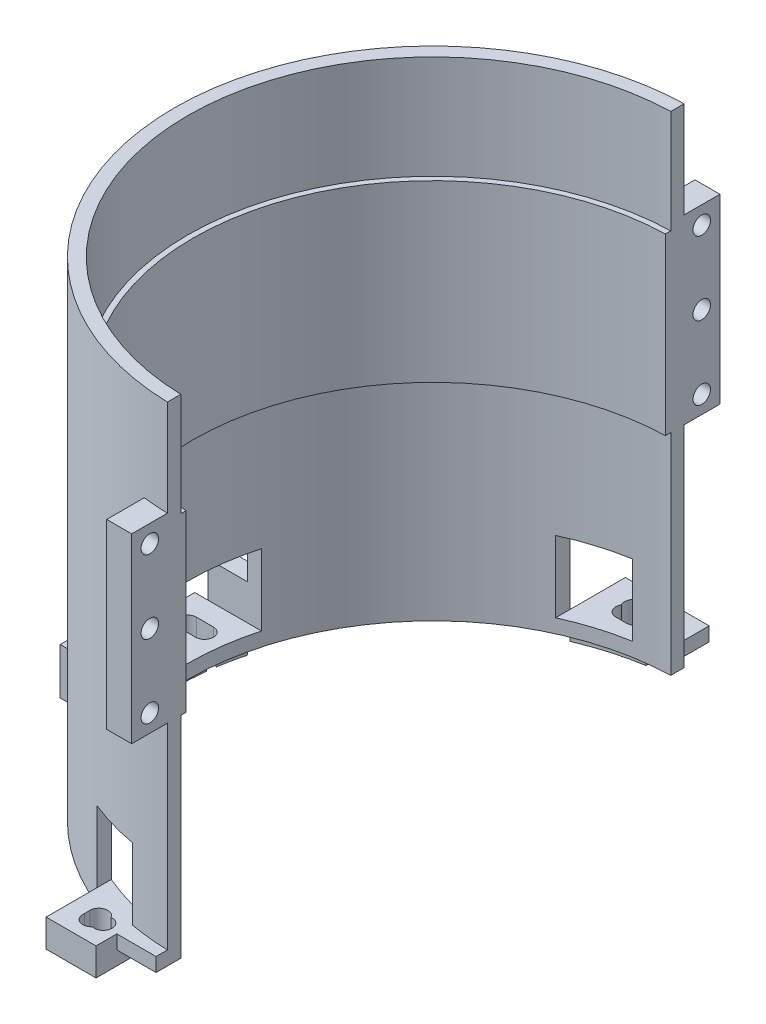
SolidWorks part; units mm, degrees
material "PLA"
ref_plane "Front Plane" through (0, 0, 0) normal (0, 0, 1) x (1, 0, 0)
ref_plane "Top Plane" through (0, 0, 0) normal (0, 1, 0) x (1, 0, 0)
ref_plane "Right Plane" through (0, 0, 0) normal (1, 0, 0) x (0, 0, -1)
sketch "Sketch1" plane through (0, 0, 0) normal (0, 1, 0) x (1, 0, 0)
  line L0 (0, 72.5) -> (0, -72.5) construction
  line L3 (0, -67.5) -> (0, -82.3274)
  line L4 (0, -82.3274) -> (-5, -82.3274)
  line L5 (-5, -72.3274) -> (-5, -82.3274)
  line L7 (0, 67.5) -> (0, 82.5)
  line L8 (0, 82.5) -> (-5, 82.5)
  line L9 (-5, 72.3274) -> (-5, 82.5)
  arc A0 (0, 67.5) -> (0, -67.5) centre (0, 0) ccw
  arc A1 (-5, 72.3274) -> (-5, -72.3274) centre (0, 0) ccw
  point P10 (-5, -72.3274)
  dimension "D1" = 135
  dimension "D2" = 145
  dimension "D3" = 10
  dimension "D4" = 10
  dimension "D5" = 5
  dimension "D6" = 5
extrude "Boss-Extrude1" add sketch "Sketch1" along normal blind 10
sketch "Sketch2" plane through (0, 0, 0) normal (0, -1, 0) x (1, 0, 0)
  line L0 (0, 72.5) -> (0, 68.5)
  line L2 (0, -72.5) -> (0, -68.5)
  arc A0 (0, 68.5) -> (0, -68.5) centre (0, 0) ccw
  arc A1 (0, 72.5) -> (0, -72.5) centre (0, 0) ccw
  dimension "D1" = 137
extrude "Boss-Extrude2" add sketch "Sketch2" along normal blind 73
sketch "Sketch3" plane through (0, -73, 0) normal (0, -1, 0) x (1, 0, 0)
  line L0 (-20.25, -68.5) -> (-20.25, 92.8167) construction
  line L2 (-85.75, 30.25) -> (-85.75, -30.25)
  line L3 (-85.75, -30.25) -> (-65.25, -30.25)
  line L9 (-20.25, -89) -> (20.25, -68.5) construction
  line L10 (-20.25, -68.5) -> (20.25, -89) construction
  line L11 (0, 0) -> (-113.2358, 0) construction
  line L13 (-25.25, -67.9609) -> (-25.25, -68.5)
  line L14 (-63.3537, -35.25) -> (-65.25, -35.25)
  line L15 (-65.25, -30.25) -> (-65.25, -126.0931) construction
  line L16 (-20.25, -68.5) -> (-129.7637, -68.5) construction
  line L18 (-59.5558, -52.1992) -> (-60.8059, -54.3063) construction
  line L19 (-59.5558, -52.1992) -> (-48.9492, -62.8058) construction
  line L20 (-54.2525, -57.5025) -> (-63.6883, -66.9383) construction
  line L21 (-59.5558, -52.1992) -> (-61.9488, -51.6738) construction
  line L23 (-65.25, -68.5) -> (-50.6267, -53.8767) construction
  line L25 (-48.9492, -62.8058) -> (-46.5562, -63.3312) construction
  line L44 (0, -69.5) -> (0, -88)
  line L45 (-84.75, 29.25) -> (-66.3377, 29.25)
  line L46 (-84.75, 29.25) -> (-84.75, -29.25)
  line L47 (-84.75, -29.25) -> (-66.3377, -29.25)
  line L49 (19.25, -69.5) -> (18.2744, -69.5)
  line L51 (19.25, -88) -> (18.2744, -88)
  line L52 (-19.25, -69.5) -> (-19.25, -88)
  line L53 (19.25, -69.5) -> (-19.25, -88) construction
  line L54 (19.25, -88) -> (-19.25, -69.5) construction
  line L55 (0, -69.5) -> (-19.25, -69.5)
  line L56 (0, -88) -> (-19.25, -88)
  line L57 (0, 69.5) -> (-19.25, 69.5)
  line L58 (0, 69.5) -> (0, 88)
  line L59 (0, 88) -> (-19.25, 88)
  line L60 (-19.25, 69.5) -> (-19.25, 88)
  arc A1 (0, 72.5) -> (0, -72.5) centre (0, 0) ccw construction
  circle A9 centre (-75.5, 20) radius 2.5
  circle A10 centre (-75.5, 0) radius 2.5
  circle A11 centre (-75.5, -20) radius 2.5
  arc A12 (-66.3377, 29.25) -> (-66.3377, -29.25) centre (0, 0) ccw
  circle A13 centre (-10, -78.75) radius 2.5
  circle A14 centre (-10, 78.75) radius 2.5
  point P1 (-20.25, -78.75)
  point P7 (-95, 0)
  point P8 (-85.75, 0)
  point P9 (0, -95)
  point P10 (0, -78.75)
  point P15 (0, -89)
  point P22 (0, -78.75)
  point P39 (-58.7595, -62.0095)
  point P42 (-54.2525, -57.5025)
  point P68 (-75.5, 29.25)
  point P70 (-75.5, -29.25)
  dimension "D21" = 5
  dimension "D22" = 5
  dimension "D23" = 5
  dimension "D8" = 5
  dimension "D2" = 60.5
  dimension "D3" = 20.5
  dimension "D4" = 9.25
  dimension "D5" = 20.5
  dimension "D6" = 40.5
  dimension "D9" = 1
  dimension "D11" = 5
  dimension "D17" = 45
  dimension "D19" = 1
  dimension "D20" = 58.5
  dimension "D25" = 20
  dimension "D26" = 20
sketch "Sketch4" plane through (0, -73, 0) normal (0, -1, 0) x (1, 0, 0)
  line L0 (0, 0) -> (0, -95) construction
  line L1 (-68.5, -20.1966) -> (-89, -20.1966)
  line L2 (-68.5, -20.1966) -> (-68.5, 20.3034)
  line L3 (-68.5, 20.3034) -> (-89, 20.3034)
  line L4 (-89, -20.1966) -> (-89, 20.3034)
  line L5 (-68.5, -20.1966) -> (-89, 20.3034) construction
  line L6 (-68.5, 20.3034) -> (-89, -20.1966) construction
  line L7 (-70.1515, 18.3034) -> (-87, 18.3034)
  line L8 (-30.25, -85.75) -> (30.25, -85.75)
  line L9 (-30.25, -85.75) -> (-30.25, -65.25)
  line L10 (-30.25, -65.25) -> (30.25, -65.25)
  line L11 (30.25, -85.75) -> (30.25, -65.25)
  line L12 (-30.25, -85.75) -> (30.25, -65.25) construction
  line L13 (-30.25, -65.25) -> (30.25, -85.75) construction
  line L14 (-30.25, 65.25) -> (30.25, 65.25)
  line L15 (-30.25, 65.25) -> (-30.25, 85.75)
  line L16 (-30.25, 85.75) -> (30.25, 85.75)
  line L17 (30.25, 65.25) -> (30.25, 85.75)
  line L18 (-30.25, 65.25) -> (30.25, 85.75) construction
  line L19 (-30.25, 85.75) -> (30.25, 65.25) construction
  line L20 (-87, 18.3034) -> (-87, -18.1966)
  line L21 (-87, -18.1966) -> (-70.1793, -18.1966)
  line L22 (-28.25, -66.7697) -> (-28.25, -83.75)
  line L23 (-28.25, -83.75) -> (-11.75, -83.75)
  line L24 (-11.75, -83.75) -> (-11.75, -71.5415)
  line L25 (-27, 67.2848) -> (-27, 80)
  line L26 (-27, 80) -> (-13, 80)
  line L27 (-13, 80) -> (-13, 71.325)
  circle A0 centre (0, 0) radius 95
  circle A1 centre (-78.75, 10.0534) radius 2.5
  circle A2 centre (-78.75, -9.9466) radius 2.5
  arc A3 (0, 72.5) -> (0, -72.5) centre (0, 0) ccw construction
  arc A4 (-70.1515, 18.3034) -> (-70.1793, -18.1966) centre (0, 0) ccw
  circle A5 centre (-20, -75.5) radius 2.5
  arc A6 (-28.25, -66.7697) -> (-11.75, -71.5415) centre (0, 0) ccw
  circle A7 centre (-20, 73) radius 2.5
  arc A8 (-27, 67.2848) -> (-13, 71.325) centre (0, 0) cw
  point P3 (-78.75, 0.0534)
  point P8 (-95, 0)
  point P10 (0, -75.5)
  point P15 (0, 75.5)
  point P16 (0, -95)
  point P22 (0, 95)
  point P26 (-78.75, 20.3034)
  point P37 (-30.25, -75.5)
  arc M22 (0, 72.5) -> (0, -72.5) centre (0, 0) ccw
  dimension "D1" = 190
  dimension "D11" = 5
  dimension "D12" = 5
  dimension "D13" = 10.25
  dimension "D18" = 5
  dimension "D23" = 5
  dimension "D2" = 20.5
  dimension "D3" = 40.5
  dimension "D4" = 26.5
  dimension "D5" = 20.5
  dimension "D6" = 60.5
  dimension "D7" = 29.75
  dimension "D8" = 20.5
  dimension "D9" = 60.5
  dimension "D10" = 29.75
  dimension "D14" = 10.25
  dimension "D15" = 2
  dimension "D16" = 2
  dimension "D17" = 2
  dimension "D19" = 10.25
  dimension "D20" = 2
  dimension "D21" = 2
  dimension "D22" = 8.25
  dimension "D24" = 73
  dimension "D25" = 20
  dimension "D26" = 7
  dimension "D27" = 7
  dimension "D28" = 7
extrude "Boss-Extrude3" add sketch "Sketch4" along normal mid plane 7.8 contours L27 L26 L25 A7 M22 | L20 L21 L7 A2 A1 M22 | L23 L24 L22 A5 M22
sketch "Sketch5" plane through (0, -69.1, 0) normal (0, 1, 0) x (1, 0, 0)
  circle A0 centre (-20, 75.5) radius 2.5 construction
  point P0 (-17.5, 75.5)
  point P1 (0, 0)
sketch "Sketch6" plane through (-5, 0, 0) normal (-1, 0, 0) x (0, 0, 1)
  line L0 (-77.4137, 10) -> (-77.4137, 5) construction
  line L1 (-82.5, 10) -> (-72.3274, 10) construction
  line L2 (-77.4137, 5) -> (-82.5, 5) construction
  line L3 (-82.5, 10) -> (-82.5, 0) construction
  line L4 (82.3274, 10) -> (82.3274, 0) construction
  line L6 (77.4124, 5) -> (72.3274, 5) construction
  line L7 (72.3274, 10) -> (72.3274, 0) construction
  circle A0 centre (77.4124, 5) radius 2.45
  circle A1 centre (-77.4137, 5) radius 2.45
  dimension "D1" = 4.9
  dimension "D2" = 4.9
  dimension "D3" = 4.915
extrude "Cut-Extrude1" cut sketch "Sketch6" against normal blind 13.9
sketch "Sketch7" plane through (0, 0, 80) normal (0, 0, 1) x (1, 0, 0)
  line L1 (-27, -69.1) -> (-13, -69.1)
  line L2 (-27, -69.1) -> (-27, -49.1)
  line L3 (-27, -49.1) -> (-13, -49.1)
  line L4 (-13, -69.1) -> (-13, -49.1)
  dimension "D1" = 20
extrude "Cut-Extrude2" cut sketch "Sketch7" against normal blind 23.9
sketch "Sketch8" plane through (0, -69.1, 0) normal (0, 1, 0) x (1, 0, 0)
  circle A0 centre (-20, -73) radius 4.8698
sketch "Sketch10" plane through (0, -69.1, 0) normal (0, 1, 0) x (1, 0, 0)
  line L0 (-13, -71.325) -> (-13, -75.6625)
  line L1 (-13, -80) -> (-13, -71.325) construction
  line L2 (-13, -75.6625) -> (0, -75.6625)
  line L3 (0, -75.6625) -> (0, -72.5)
  arc A0 (-13, -71.325) -> (0, -72.5) centre (0, 0) ccw construction
  arc A1 (-13, -71.325) -> (0, -72.5) centre (0, 0) ccw
extrude "Boss-Extrude4" add sketch "Sketch10" against normal blind 3.9
sketch "Sketch11" plane through (0, 10, 0) normal (0, 1, 0) x (1, 0, 0)
  line L0 (0, 82.5) -> (0, -82.3274) construction
  circle A0 centre (0, 0.0863) radius 67.4137
sketch "Sketch12" plane through (0, 0, 82.3274) normal (0, 0, 1) x (1, 0, 0)
  line L4 (-5, 0) -> (0, 0)
  line L5 (0, 0) -> (0, 10)
  line L6 (0, 10) -> (-5, 10)
  line L7 (-5, 10) -> (-5, 0)
  line L8 (-5, 0) -> (0, 0)
  line L9 (0, 0) -> (0, 10)
  line L10 (0, 10) -> (-5, 10)
  line L11 (-5, 10) -> (-5, 0)
  dimension "D1" = 0
extrude "Boss-Extrude5" add sketch "Sketch12" along normal blind 0.17
sketch "Sketch13" plane through (0, -73, 0) normal (0, -1, 0) x (1, 0, 0)
  circle A0 centre (0, 0) radius 68.75
  dimension "D1" = 137.5
extrude "Cut-Extrude3" cut sketch "Sketch13" against normal up to surface (73 mm away) up to face at (-34, 0, 0)
sketch "Sketch14" plane through (0, 10, 0) normal (0, 1, 0) x (1, 0, 0)
  line L6 (-5, -72.3274) -> (-5, -82.4974)
  line L7 (-5, -82.4974) -> (0, -82.4974)
  line L8 (0, -82.4974) -> (0, -67.5)
  line L9 (0, 67.5) -> (0, 82.5)
  line L10 (0, 82.5) -> (-5, 82.5)
  line L11 (-5, 82.5) -> (-5, 72.3274)
  line L12 (-5, -72.3274) -> (-5, -82.4974)
  line L13 (-5, -82.4974) -> (0, -82.4974)
  line L14 (0, -82.4974) -> (0, -67.5)
  line L15 (0, 67.5) -> (0, 82.5)
  line L16 (0, 82.5) -> (-5, 82.5)
  line L17 (-5, 82.5) -> (-5, 72.3274)
  arc A2 (-5, 72.3274) -> (-5, -72.3274) centre (0, 0) ccw
  arc A3 (0, 67.5) -> (0, -67.5) centre (0, 0) ccw
  arc A4 (-5, 72.3274) -> (-5, -72.3274) centre (0, 0) ccw
  arc A5 (0, 67.5) -> (0, -67.5) centre (0, 0) ccw
  dimension "D1" = 0
extrude "Boss-Extrude6" add sketch "Sketch14" along normal blind 27
sketch "Sketch15" plane through (0, 37, 0) normal (0, 1, 0) x (1, 0, 0)
  line L0 (0, -68.75) -> (0, -72.5)
  line L1 (0, 68.75) -> (0, -68.2) construction
  line L2 (0, 68.75) -> (0, 68.2)
  line L3 (0, -68.75) -> (0, -68.2)
  line L4 (0, -75.6625) -> (0, -68.75)
  line L5 (-13, -75.6625) -> (0, -75.6625)
  line L6 (-13, -71.325) -> (-13, -75.6625)
  line L7 (0, 68.75) -> (0, 72.5)
  line L11 (0, 68.75) -> (0, 72.5)
  arc A0 (-13, -71.325) -> (0, -72.5) centre (0, 0) ccw construction
  arc A1 (-13, -71.325) -> (0, -72.5) centre (0, 0) ccw
  arc A2 (0, 68.2) -> (0, -68.2) centre (0, 0) ccw
  arc A7 (0, 68.75) -> (0, -68.75) centre (0, 0) ccw
  arc A8 (-27, -67.2848) -> (-13, -71.325) centre (0, 0) ccw
  arc A9 (-70.1515, -18.3034) -> (-27, -67.2848) centre (0, 0) ccw
  arc A10 (-70.1793, 18.1966) -> (-70.1515, -18.3034) centre (0, 0) ccw
  arc A11 (-28.25, 66.7697) -> (-70.1793, 18.1966) centre (0, 0) ccw
  arc A12 (-11.75, 71.5415) -> (-28.25, 66.7697) centre (0, 0) ccw
  arc A13 (0, 72.5) -> (-11.75, 71.5415) centre (0, 0) ccw
  arc A14 (0, 68.75) -> (0, -68.75) centre (0, 0) ccw
  arc A15 (-27, -67.2848) -> (-13, -71.325) centre (0, 0) ccw
  arc A16 (-70.1515, -18.3034) -> (-27, -67.2848) centre (0, 0) ccw
  arc A17 (-70.1793, 18.1966) -> (-70.1515, -18.3034) centre (0, 0) ccw
  arc A18 (-28.25, 66.7697) -> (-70.1793, 18.1966) centre (0, 0) ccw
  arc A19 (-11.75, 71.5415) -> (-28.25, 66.7697) centre (0, 0) ccw
  arc A20 (0, 72.5) -> (-11.75, 71.5415) centre (0, 0) ccw
  arc M14 (-5, 72.3274) -> (-5, -72.3274) centre (0, 0) ccw
  line M17 (0, -82.4974) -> (0, -67.5)
  line M19 (0, 67.5) -> (0, 82.5)
  dimension "D2" = 136.4
  dimension "D1" = 0
extrude "Boss-Extrude7" add sketch "Sketch15" along normal blind 27 contours A20 A1 A14 M19 M14 M17 | A14 A2 M19 M17
sketch "Sketch16" plane through (0, -73, 0) normal (0, -1, 0) x (1, 0, 0)
  line L2 (0, -68.2) -> (0, -67.5)
  line L3 (0, 67.5) -> (0, 68.2)
  line L4 (0, -68.2) -> (0, -67.5)
  line L5 (0, 67.5) -> (0, 68.2)
  arc A2 (0, 68.2) -> (0, -68.2) centre (0, 0) ccw
  arc A3 (0, 67.5) -> (0, -67.5) centre (0, 0) ccw
  arc A4 (0, 68.2) -> (0, -68.2) centre (0, 0) ccw
  arc A5 (0, 67.5) -> (0, -67.5) centre (0, 0) ccw
  dimension "D1" = 0
sketch "Sketch17" plane through (0, 0, 0) normal (0, -1, 0) x (1, 0, 0)
  line L0 (0, 68.2) -> (0, 68.75)
  line L1 (0, -68.2) -> (0, -68.75)
  line L2 (0, -68.2) -> (0, -67.5)
  line L3 (0, 67.5) -> (0, 68.2)
  arc A0 (0, 68.75) -> (0, -68.75) centre (0, 0) ccw construction
  arc A1 (0, 68.75) -> (0, -68.75) centre (0, 0) ccw
  arc A2 (0, 68.2) -> (0, -68.2) centre (0, 0) ccw
  arc A3 (0, 67.5) -> (0, -67.5) centre (0, 0) ccw
  arc A4 (0, 68.2) -> (0, -68.2) centre (0, 0) ccw
  dimension "D1" = 0
extrude "Boss-Extrude8" add sketch "Sketch17" along normal up to surface (73 mm away) up to face at (-28.7427, -73, 7.1905)
sketch "Sketch18" plane through (0, 37, 0) normal (0, 1, 0) x (1, 0, 0)
  line L0 (0, 67.5) -> (0, -67.25) construction
  line L1 (0, -67.25) -> (0, -67.5)
  line L2 (0, 67.5) -> (0, 67.25)
  arc A0 (0, 67.25) -> (0, -67.25) centre (0, 0) ccw
  arc A2 (0, 67.5) -> (0, -67.5) centre (0, 0) ccw construction
  arc A3 (0, 67.5) -> (0, -67.5) centre (0, 0) ccw
  dimension "D1" = 134.5
extrude "Boss-Extrude9" add sketch "Sketch18" against normal up to surface (37 mm away) up to face at (-2.5004, 0, -77.4676)
sketch "Sketch19" plane through (0, 0, 0) normal (0, -1, 0) x (1, 0, 0)
  line L2 (0, -68.2) -> (0, -67.25)
  line L3 (0, 67.25) -> (0, 68.2)
  line L4 (0, -68.2) -> (0, -67.25)
  line L5 (0, 67.25) -> (0, 68.2)
  arc A2 (0, 68.2) -> (0, -68.2) centre (0, 0) ccw
  arc A3 (0, 67.25) -> (0, -67.25) centre (0, 0) ccw
  arc A4 (0, 68.2) -> (0, -68.2) centre (0, 0) ccw
  arc A5 (0, 67.25) -> (0, -67.25) centre (0, 0) ccw
  dimension "D1" = 0
extrude "Boss-Extrude10" add sketch "Sketch19" along normal blind 14
sketch "Sketch20" plane through (0, 37, 0) normal (0, 1, 0) x (1, 0, 0)
  line L2 (0, 67.25) -> (0, 68.2)
  line L3 (0, -68.2) -> (0, -67.25)
  line L4 (0, 67.25) -> (0, 68.2)
  line L5 (0, -68.2) -> (0, -67.25)
  arc A2 (0, 68.2) -> (0, -68.2) centre (0, 0) ccw
  arc A3 (0, 67.25) -> (0, -67.25) centre (0, 0) ccw
  arc A4 (0, 68.2) -> (0, -68.2) centre (0, 0) ccw
  arc A5 (0, 67.25) -> (0, -67.25) centre (0, 0) ccw
  dimension "D1" = 0
extrude "Cut-Extrude4" cut sketch "Sketch20" against normal blind 2
sketch "Sketch21" plane through (0, 0, 80) normal (0, 0, 1) x (1, 0, 0)
  line L4 (-13, -49.1) -> (-27, -49.1)
  line L5 (-27, -49.1) -> (-27, -69.1)
  line L6 (-27, -69.1) -> (-13, -69.1)
  line L7 (-13, -69.1) -> (-13, -49.1)
  line L8 (-13, -49.1) -> (-27, -49.1)
  line L9 (-27, -49.1) -> (-27, -69.1)
  line L10 (-27, -69.1) -> (-13, -69.1)
  line L11 (-13, -69.1) -> (-13, -49.1)
  dimension "D1" = 0
extrude "Cut-Extrude5" cut sketch "Sketch21" against normal blind 22
sketch "Sketch23" plane through (0, 0, 0) normal (0, -1, 0) x (1, 0, 0)
  line L3 (0, 72.5) -> (0, 82.4974)
  line L4 (0, 82.4974) -> (-5, 82.4974)
  line L5 (-5, 82.4974) -> (-5, 72.3274)
  line L6 (0, 72.5) -> (0, 82.4974)
  line L7 (0, 82.4974) -> (-5, 82.4974)
  line L8 (-5, 82.4974) -> (-5, 72.3274)
  arc A1 (0, 72.5) -> (-5, 72.3274) centre (0, 0) ccw
  arc A2 (0, 72.5) -> (-5, 72.3274) centre (0, 0) ccw
  dimension "D1" = 0
extrude "Boss-Extrude11" add sketch "Sketch23" along normal up to surface (14 mm away) up to face at (-33.8625, -14, 0)
sketch "Sketch24" plane through (0, 0, 0) normal (1, 0, 0) x (0, 0, -1)
  line L0 (-77.4124, 5) -> (-77.4124, -14) construction
  line L1 (-72.5, -14) -> (-82.4974, -14) construction
  line L2 (-77.4124, 5) -> (-77.4124, 37) construction
  line L3 (-82.4974, 37) -> (-72.5, 37) construction
  circle A0 centre (-77.4124, -9.05) radius 2.45
  circle A1 centre (-77.4124, 32.05) radius 2.45
  circle A2 centre (-77.4124, 11.5) radius 2.45
  point P10 (-77.4124, -11.5)
  point P13 (-77.4124, 34.5)
  dimension "D1" = 4.9
  dimension "D3" = 4.9
  dimension "D5" = 4.9
  dimension "D2" = 2.5
  dimension "D4" = 2.5
  dimension "D6" = 25.5
sketch "Sketch25" plane through (0, 0, 0) normal (1, 0, 0) x (0, 0, -1)
  circle A0 centre (-77.4124, 5) radius 2.45
extrude "Boss-Extrude12" add sketch "Sketch25" against normal up to surface (5 mm away) up to face at (-5, 5, 79.8624)
extrude "Cut-Extrude6" cut sketch "Sketch24" against normal blind 22 contours A0 | A1 | A2
sketch "Sketch26" plane through (0, 0, 0) normal (1, 0, 0) x (0, 0, -1)
  circle A0 centre (77.4137, 5) radius 2.45 construction
  circle A1 centre (77.4137, 5) radius 2.45
extrude "Boss-Extrude13" add sketch "Sketch26" against normal up to surface (5 mm away) up to face at (-5, 5, -74.9637)
sketch "Sketch27" plane through (0, 0, 0) normal (0, -1, 0) x (1, 0, 0)
  line L3 (-5, -72.3274) -> (-5, -82.5)
  line L4 (-5, -82.5) -> (0, -82.5)
  line L5 (0, -82.5) -> (0, -72.5)
  line L6 (-5, -72.3274) -> (-5, -82.5)
  line L7 (-5, -82.5) -> (0, -82.5)
  line L8 (0, -82.5) -> (0, -72.5)
  arc A1 (-5, -72.3274) -> (0, -72.5) centre (0, 0) ccw
  arc A2 (-5, -72.3274) -> (0, -72.5) centre (0, 0) ccw
  dimension "D1" = 0
extrude "Boss-Extrude14" add sketch "Sketch27" along normal up to surface (14 mm away) up to face at (-33.8625, -14, 0)
sketch "Sketch28" plane through (0, 64, 0) normal (0, 1, 0) x (1, 0, 0)
  line L0 (-72.5, -0.0552) -> (-33.8601, -0.0552) construction
  arc A0 (-70.1793, 18.1966) -> (-70.1515, -18.3034) centre (0, 0) ccw construction
ref_plane "Plane2" through (0, 0, 0.0552) normal (0, 0, 1) x (1, 0, 0)
sketch "Sketch29" plane through (0, 0, 0) normal (1, 0, 0) x (0, 0, -1)
  line L0 (82.5, 37) -> (82.5, -14) construction
  line L1 (72.5, 37) -> (82.5, 37) construction
  circle A0 centre (77.41, 32.05) radius 2.45
  circle A1 centre (77.41, 11.5) radius 2.45
  circle A2 centre (77.41, -9.05) radius 2.45
  dimension "D1" = 4.9
  dimension "D2" = 4.9
  dimension "D3" = 4.9
  dimension "D6" = 20.55
  dimension "D4" = 5.09
  dimension "D5" = 4.95
  dimension "D7" = 20.55
extrude "Cut-Extrude7" cut sketch "Sketch29" against normal blind 22
sketch "Sketch30" plane through (0, -69.1, 0) normal (0, 1, 0) x (1, 0, 0)
  circle A0 centre (-20, -75.71) radius 2.5
  dimension "D1" = 5
  dimension "D2" = 2.71
sketch "Sketch31" plane through (0, -69.1, 0) normal (0, 1, 0) x (1, 0, 0)
  circle A0 centre (-20, -73) radius 2.5 construction
  circle A1 centre (-20, -73) radius 2.5
extrude "Boss-Extrude15" add sketch "Sketch31" against normal up to surface (7.8 mm away) up to face at (-20, -76.9, 70.5)
extrude "Cut-Extrude8" cut sketch "Sketch30" against normal blind 30 contours A0
sketch "Sketch32" plane through (0, 0, 80) normal (0, 0, 1) x (1, 0, 0)
  line L4 (-13, -69.1) -> (-27, -69.1)
  line L5 (-27, -69.1) -> (-27, -76.9)
  line L6 (-27, -76.9) -> (-13, -76.9)
  line L7 (-13, -76.9) -> (-13, -69.1)
  line L8 (-13, -69.1) -> (-27, -69.1)
  line L9 (-27, -69.1) -> (-27, -76.9)
  line L10 (-27, -76.9) -> (-13, -76.9)
  line L11 (-13, -76.9) -> (-13, -69.1)
  dimension "D1" = 0
extrude "Boss-Extrude16" add sketch "Sketch32" along normal blind 1.5
sketch "Sketch33" plane through (0, -69.1, 0) normal (0, 1, 0) x (1, 0, 0)
  circle A0 centre (-20, 75.5) radius 2.5 construction
  circle A1 centre (-20, 75.5) radius 2.5
sketch "Sketch34" plane through (0, -69.1, 0) normal (0, 1, 0) x (1, 0, 0)
  circle A0 centre (-20, 73.79) radius 2.5
  dimension "D1" = 5
  dimension "D2" = 1.71
extrude "Boss-Extrude18" add sketch "Sketch33" against normal up to surface (7.8 mm away) up to face at (-20, -76.9, -78)
extrude "Cut-Extrude9" cut sketch "Sketch34" against normal blind 31.5 contours A0
sketch "Sketch35" plane through (0, 0, -83.75) normal (0, 0, -1) x (-1, 0, 0)
  line L1 (11.75, -69.1) -> (28.25, -69.1)
  line L2 (11.75, -69.1) -> (11.75, -49.1)
  line L3 (11.75, -49.1) -> (28.25, -49.1)
  line L4 (28.25, -69.1) -> (28.25, -49.1)
  dimension "D1" = 20
extrude "Cut-Extrude10" cut sketch "Sketch35" against normal blind 31.5
sketch "Sketch36" plane through (-11.75, 0, 0) normal (1, 0, 0) x (0, 0, -1)
  line L1 (83.75, -69.1) -> (71.5415, -69.1)
  line L2 (83.75, -69.1) -> (83.75, -73)
  line L3 (83.75, -73) -> (71.5415, -73)
  line L4 (71.5415, -69.1) -> (71.5415, -73)
extrude "Boss-Extrude19" add sketch "Sketch36" along normal blind 7
sketch "Sketch38" plane through (0, 0, 0) normal (1, 0, 0) x (0, 0, -1)
  line L1 (-108.641, 75.8632) -> (-59.3344, 75.8632)
  line L2 (-108.641, 75.8632) -> (-108.641, -80.1618)
  line L3 (-108.641, -80.1618) -> (-59.3344, -80.1618)
  line L4 (-59.3344, 75.8632) -> (-59.3344, -80.1618)
  line L5 (103.4449, 80.1409) -> (46.7085, 80.1409)
  line L6 (103.4449, 80.1409) -> (103.4449, -81.5126)
  line L7 (103.4449, -81.5126) -> (46.7085, -81.5126)
  line L8 (46.7085, 80.1409) -> (46.7085, -81.5126)
extrude "Cut-Extrude11" cut sketch "Sketch38" against normal blind 2
sketch "Sketch39" plane through (-5, 0, 0) normal (-1, 0, 0) x (0, 0, 1)
  line L1 (72.3274, 37) -> (71.4796, 37)
  line L2 (72.3274, 37) -> (72.3274, -14)
  line L3 (72.3274, -14) -> (71.4796, -14)
  line L4 (72.3274, 37) -> (72.3274, -14)
  line L5 (72.3274, -14) -> (82.4974, -14)
  line L6 (82.4974, -14) -> (82.4974, 37)
  line L7 (82.4974, 37) -> (72.3274, 37)
  line L8 (72.3274, 37) -> (72.3274, -14)
  line L9 (72.3274, -14) -> (82.4974, -14)
  line L10 (82.4974, -14) -> (82.4974, 37)
  line L11 (82.4974, 37) -> (72.3274, 37)
  line L12 (71.4796, 37) -> (71.4796, -14)
  line L13 (-72.3274, 37) -> (-71.1862, 37)
  line L14 (-72.3274, 37) -> (-72.3274, -14)
  line L15 (-72.3274, -14) -> (-71.1862, -14)
  line L16 (-82.5, 37) -> (-82.5, -14)
  line L17 (-82.5, -14) -> (-72.3274, -14)
  line L18 (-72.3274, -14) -> (-72.3274, 37)
  line L19 (-72.3274, 37) -> (-82.5, 37)
  line L20 (-82.5, 37) -> (-82.5, -14)
  line L21 (-82.5, -14) -> (-72.3274, -14)
  line L22 (-72.3274, -14) -> (-72.3274, 37)
  line L23 (-72.3274, 37) -> (-82.5, 37)
  line L24 (-71.1862, 37) -> (-71.1862, -14)
  circle A0 centre (77.4124, -9.05) radius 2.45 construction
  circle A1 centre (77.4124, 11.5) radius 2.45 construction
  circle A2 centre (77.4124, 32.05) radius 2.45 construction
  circle A3 centre (-77.41, -9.05) radius 2.45 construction
  circle A4 centre (-77.41, 11.5) radius 2.45 construction
  circle A5 centre (-77.41, 32.05) radius 2.45 construction
  circle A6 centre (77.4124, -9.05) radius 2.45
  circle A7 centre (77.4124, 11.5) radius 2.45
  circle A8 centre (77.4124, 32.05) radius 2.45
  circle A9 centre (-77.41, -9.05) radius 2.45
  circle A10 centre (-77.41, 11.5) radius 2.45
  circle A11 centre (-77.41, 32.05) radius 2.45
  dimension "D1" = 0
  dimension "D2" = 0
sketch "Sketch40" plane through (-5, 0, 0) normal (-1, 0, 0) x (0, 0, 1)
  line L1 (82.4974, 37) -> (70.5875, 37)
  line L2 (82.4974, 37) -> (82.4974, -14)
  line L3 (82.4974, -14) -> (70.5875, -14)
  line L4 (70.5875, 37) -> (70.5875, -14)
  line L5 (-82.5, 37) -> (-69.0553, 37)
  line L6 (-82.5, 37) -> (-82.5, -14)
  line L7 (-82.5, -14) -> (-69.0553, -14)
  line L8 (-69.0553, 37) -> (-69.0553, -14)
  circle A0 centre (77.4124, -9.05) radius 2.45 construction
  circle A1 centre (77.4124, 11.5) radius 2.45 construction
  circle A2 centre (77.4124, 32.05) radius 2.45 construction
  circle A3 centre (-77.41, -9.05) radius 2.45 construction
  circle A4 centre (-77.41, 11.5) radius 2.45 construction
  circle A5 centre (-77.41, 32.05) radius 2.45 construction
  circle A6 centre (77.4124, -9.05) radius 2.45
  circle A7 centre (77.4124, 11.5) radius 2.45
  circle A8 centre (77.4124, 32.05) radius 2.45
  circle A9 centre (-77.41, -9.05) radius 2.45
  circle A10 centre (-77.41, 11.5) radius 2.45
  circle A11 centre (-77.41, 32.05) radius 2.45
extrude "Boss-Extrude20" add sketch "Sketch40" along normal blind 4
sketch "Sketch41" plane through (0, -69.1, 0) normal (0, 1, 0) x (1, 0, 0)
  line L0 (-74.0108, 12.4466) -> (-78.75, 12.4466)
  line L1 (-74.0108, 7.4466) -> (-78.75, 7.4466)
  line L2 (-78.75, 12.4466) -> (-78.75, 7.4466)
  line L3 (-87, -0.0534) -> (-75.0669, -0.0534) construction
  line L4 (-87, -18.3034) -> (-87, 18.1966) construction
  line L5 (-74.0108, -12.5534) -> (-78.75, -12.5534)
  line L6 (-74.0108, -7.5534) -> (-78.75, -7.5534)
  line L7 (-78.75, -12.5534) -> (-78.75, -7.5534)
  arc A2 (-74.0108, 7.4466) -> (-74.0108, 12.4466) centre (-74.0108, 9.9466) ccw
  circle A3 centre (-78.75, 9.9466) radius 2.5 construction
  arc A4 (-74.0108, -7.5534) -> (-74.0108, -12.5534) centre (-74.0108, -10.0534) cw
  circle M3 centre (-78.75, -10.0534) radius 2.5
  arc M6 (-70.1515, -18.3034) -> (-70.1793, 18.1966) centre (0, 0) cw
  dimension "D1" = 5
extrude "Cut-Extrude12" cut sketch "Sketch41" against normal blind 12 contours A4 L6 L5 M3 M6 | L7 M3 | L1 L2 L0 A2
sketch "Sketch42" plane through (-87, 0, 0) normal (-1, 0, 0) x (0, 0, 1)
  line L1 (-18.1966, -69.1) -> (18.3034, -69.1)
  line L2 (-18.1966, -69.1) -> (-18.1966, -49.1)
  line L3 (-18.1966, -49.1) -> (18.3034, -49.1)
  line L4 (18.3034, -69.1) -> (18.3034, -49.1)
  dimension "D1" = 20
extrude "Cut-Extrude14" cut sketch "Sketch42" against normal blind 42
sketch "Sketch43" plane through (0, -69.1, 0) normal (0, 1, 0) x (1, 0, 0)
  line L0 (-81.25, -18.3034) -> (-81.25, -23.3034)
  line L1 (-70.1515, -18.3034) -> (-87, -18.3034) construction
  line L2 (-81.25, -23.3034) -> (-68.6528, -23.3034)
  line L3 (-81.25, -18.3034) -> (-70.1515, -18.3034)
  line L4 (-81.25, 18.1966) -> (-81.25, 23.1966)
  line L5 (-87, 18.1966) -> (-70.1793, 18.1966) construction
  line L6 (-81.25, 23.1966) -> (-68.6889, 23.1966)
  line L7 (-81.25, 18.1966) -> (-70.1793, 18.1966)
  arc A0 (-2, 72.4724) -> (-2, -72.4724) centre (0, 0) ccw construction
  arc A1 (-68.6889, 23.1966) -> (-70.1793, 18.1966) centre (0, 0) ccw
  arc A2 (-70.1515, -18.3034) -> (-68.6528, -23.3034) centre (0, 0) ccw
  dimension "D1" = 5
  dimension "D2" = 5
extrude "Boss-Extrude21" add sketch "Sketch43" against normal blind 3
sketch "Sketch44" plane through (0, -69.1, 0) normal (0, 1, 0) x (1, 0, 0)
  line L3 (-81.25, 23.1966) -> (-81.25, 18.1966)
  line L4 (-68.6889, 23.1966) -> (-81.25, 23.1966)
  line L5 (-81.25, 18.1966) -> (-70.1793, 18.1966)
  line L6 (-81.25, 23.1966) -> (-81.25, 18.1966)
  line L7 (-68.6889, 23.1966) -> (-81.25, 23.1966)
  line L8 (-81.25, 18.1966) -> (-70.1793, 18.1966)
  line L9 (-81.25, -18.3034) -> (-81.25, -23.3034)
  line L10 (-81.25, -23.3034) -> (-68.6528, -23.3034)
  line L11 (-70.1515, -18.3034) -> (-81.25, -18.3034)
  line L12 (-81.25, -18.3034) -> (-81.25, -23.3034)
  line L13 (-81.25, -23.3034) -> (-68.6528, -23.3034)
  line L14 (-70.1515, -18.3034) -> (-81.25, -18.3034)
  arc A1 (-68.6889, 23.1966) -> (-70.1793, 18.1966) centre (0, 0) ccw
  arc A2 (-68.6889, 23.1966) -> (-70.1793, 18.1966) centre (0, 0) ccw
  arc A3 (-70.1515, -18.3034) -> (-68.6528, -23.3034) centre (0, 0) ccw
  arc A4 (-70.1515, -18.3034) -> (-68.6528, -23.3034) centre (0, 0) ccw
  dimension "D1" = 0
  dimension "D2" = 0
extrude "Boss-Extrude22" add sketch "Sketch44" along normal blind 10
sketch "Sketch45" plane through (0, -69.1, 0) normal (0, 1, 0) x (1, 0, 0)
  line L0 (-22.5, -73.71) -> (-22.4495, -76.21)
  line L1 (-22.4495, -76.21) -> (-17.5505, -76.21)
  line L2 (-17.5505, -76.21) -> (-17.5, -73.71)
  arc A0 (-17.502, -73.811) -> (-22.498, -73.811) centre (-20, -73.71) ccw
  circle A2 centre (-20, -75.71) radius 2.5 construction
  circle A3 centre (-17.5253, -74.96) radius 2.5
  circle M2 centre (-20, -75.71) radius 2.5
  dimension "D1" = 5
  dimension "D3" = 5
  dimension "D2" = 2
extrude "Cut-Extrude15" cut sketch "Sketch45" against normal blind 23 contours A3 L0 L1 M2 | A3 L1 L2 M2 | A3 A0 L0 M2 | A0 A3 L2 M2 | A3 A0 L2 M2 | L1 A3 M2
sketch "Sketch46" plane through (0, -69.1, 0) normal (0, 1, 0) x (1, 0, 0)
  line L0 (-20, 76.29) -> (-17, 76.29)
  line L1 (-17, 71.29) -> (-20, 71.29)
  line L2 (-20, 71.29) -> (-20, 76.29)
  arc A0 (-17, 71.29) -> (-17, 76.29) centre (-17, 73.79) ccw
  circle A1 centre (-20, 73.79) radius 2.5 construction
  circle A2 centre (-20, 76.29) radius 2.5
  circle M1 centre (-20, 73.79) radius 2.5
  dimension "D1" = 5
  dimension "D3" = 5
  dimension "D2" = 3
extrude "Cut-Extrude16" cut sketch "Sketch46" against normal blind 23 contours A2 L1 A0 L0 M1 | A2 L2 M1 | L2 A2 M1
sketch "Sketch47" plane through (-87, 0, 0) normal (-1, 0, 0) x (0, 0, 1)
  line L4 (18.3034, -69.1) -> (-18.1966, -69.1)
  line L5 (-18.1966, -69.1) -> (-18.1966, -76.9)
  line L6 (-18.1966, -76.9) -> (18.3034, -76.9)
  line L7 (18.3034, -76.9) -> (18.3034, -69.1)
  line L8 (18.3034, -69.1) -> (-18.1966, -69.1)
  line L9 (-18.1966, -69.1) -> (-18.1966, -76.9)
  line L10 (-18.1966, -76.9) -> (18.3034, -76.9)
  line L11 (18.3034, -76.9) -> (18.3034, -69.1)
  dimension "D1" = 0
extrude "Cut-Extrude17" cut sketch "Sketch47" against normal blind 2
sketch "Sketch48" plane through (0, 0, -83.75) normal (0, 0, -1) x (-1, 0, 0)
  line L6 (28.25, -69.1) -> (4.75, -69.1)
  line L7 (4.75, -69.1) -> (4.75, -73)
  line L8 (4.75, -73) -> (11.75, -73)
  line L9 (11.75, -73) -> (11.75, -76.9)
  line L10 (11.75, -76.9) -> (28.25, -76.9)
  line L11 (28.25, -76.9) -> (28.25, -69.1)
  line L12 (28.25, -69.1) -> (4.75, -69.1)
  line L13 (4.75, -69.1) -> (4.75, -73)
  line L14 (4.75, -73) -> (11.75, -73)
  line L15 (11.75, -73) -> (11.75, -76.9)
  line L16 (11.75, -76.9) -> (28.25, -76.9)
  line L17 (28.25, -76.9) -> (28.25, -69.1)
  dimension "D1" = 0
extrude "Cut-Extrude18" cut sketch "Sketch48" against normal blind 1.5
sketch "Sketch49" plane through (0, 64, 0) normal (0, 1, 0) x (1, 0, 0)
  line L0 (-2, 68.1707) -> (-2, 68.7209)
  line L1 (-2, 72.4724) -> (-2, 68.1707) construction
  line L2 (-2, -68.1707) -> (-2, -68.7209)
  line L3 (-2, -72.4724) -> (-2, -68.1707) construction
  arc A0 (-2, 68.1707) -> (-2, -68.1707) centre (0, 0) ccw construction
  arc A1 (-2, 68.1707) -> (-2, -68.1707) centre (0, 0) ccw
  arc A2 (-2, 68.7209) -> (-2, -68.7209) centre (0, 0) ccw
  point P3 (0, 0)
  dimension "D1" = 137.5
extrude "Cut-Extrude19" cut sketch "Sketch49" against normal up to surface (29 mm away) contours A2 L2 A1 L0 up to face at (-34.8625, 35, 0)
sketch "Sketch50" plane through (0, -73, 0) normal (0, -1, 0) x (1, 0, 0)
  line L0 (-2, 68.1707) -> (-2, 68.7209)
  line L1 (-2, -68.1707) -> (-2, -68.7209)
  arc A1 (-2, 68.1707) -> (-2, -68.1707) centre (0, 0) ccw construction
  arc A2 (-2, 68.1707) -> (-2, -68.1707) centre (0, 0) ccw
  arc A3 (-2, 68.7209) -> (-2, -68.7209) centre (0, 0) ccw
  dimension "D1" = 137.5
extrude "Cut-Extrude20" cut sketch "Sketch50" against normal up to surface (59 mm away) up to face at (-34.8625, -14, 0)
sketch "Sketch51" plane through (-9, 0, 0) normal (-1, 0, 0) x (0, 0, 1)
  line L0 (82.4974, -14) -> (82.4974, 37) construction
  line L1 (81.6624, 29.5963) -> (81.6624, 34.5037)
  line L2 (81.6624, 34.5037) -> (77.4124, 36.9575)
  line L3 (77.4124, 36.9575) -> (73.1624, 34.5037)
  line L4 (73.1624, 34.5037) -> (73.1624, 29.5963)
  line L5 (73.1624, 29.5963) -> (77.4124, 27.1425)
  line L6 (77.4124, 27.1425) -> (81.6624, 29.5963)
  line L8 (77.4124, 16.4075) -> (73.1624, 13.9537)
  line L9 (73.1624, 13.9537) -> (73.1624, 9.0463)
  line L10 (73.1624, 9.0463) -> (77.4124, 6.5925)
  line L11 (77.4124, 6.5925) -> (81.6624, 9.0463)
  line L12 (81.6624, 9.0463) -> (81.6624, 13.9537)
  line L13 (81.6624, 13.9537) -> (77.4124, 16.4075)
  line L14 (77.4124, -4.1425) -> (73.1624, -6.5963)
  line L15 (73.1624, -6.5963) -> (73.1624, -11.5037)
  line L16 (73.1624, -11.5037) -> (77.4124, -13.9575)
  line L17 (77.4124, -13.9575) -> (81.6624, -11.5037)
  line L18 (81.6624, -11.5037) -> (81.6624, -6.5963)
  line L19 (81.6624, -6.5963) -> (77.4124, -4.1425)
  line L20 (-77.41, 36.9575) -> (-81.66, 34.5037)
  line L21 (-81.66, 34.5037) -> (-81.66, 29.5963)
  line L22 (-81.66, 29.5963) -> (-77.41, 27.1425)
  line L23 (-77.41, 27.1425) -> (-73.16, 29.5963)
  line L24 (-73.16, 29.5963) -> (-73.16, 34.5037)
  line L25 (-73.16, 34.5037) -> (-77.41, 36.9575)
  line L26 (-77.41, 16.4075) -> (-81.66, 13.9537)
  line L27 (-81.66, 13.9537) -> (-81.66, 9.0463)
  line L28 (-81.66, 9.0463) -> (-77.41, 6.5925)
  line L29 (-77.41, 6.5925) -> (-73.16, 9.0463)
  line L30 (-73.16, 9.0463) -> (-73.16, 13.9537)
  line L31 (-73.16, 13.9537) -> (-77.41, 16.4075)
  line L32 (-77.41, -4.1425) -> (-81.66, -6.5963)
  line L33 (-81.66, -6.5963) -> (-81.66, -11.5037)
  line L34 (-81.66, -11.5037) -> (-77.41, -13.9575)
  line L35 (-77.41, -13.9575) -> (-73.16, -11.5037)
  line L36 (-73.16, -11.5037) -> (-73.16, -6.5963)
  line L37 (-73.16, -6.5963) -> (-77.41, -4.1425)
  circle A0 centre (77.4124, 32.05) radius 4.25 construction
  circle A1 centre (77.4124, 11.5) radius 4.25 construction
  circle A2 centre (77.4124, -9.05) radius 4.25 construction
  circle A3 centre (-77.41, 32.05) radius 4.25 construction
  circle A4 centre (-77.41, 11.5) radius 4.25 construction
  circle A5 centre (-77.41, -9.05) radius 4.25 construction
  dimension "D1" = 8.5
  dimension "D2" = 8.5
  dimension "D3" = 8.5
  dimension "D4" = 8.5
  dimension "D5" = 8.5
  dimension "D6" = 8.5
extrude "Cut-Extrude21" cut sketch "Sketch51" against normal blind 2
